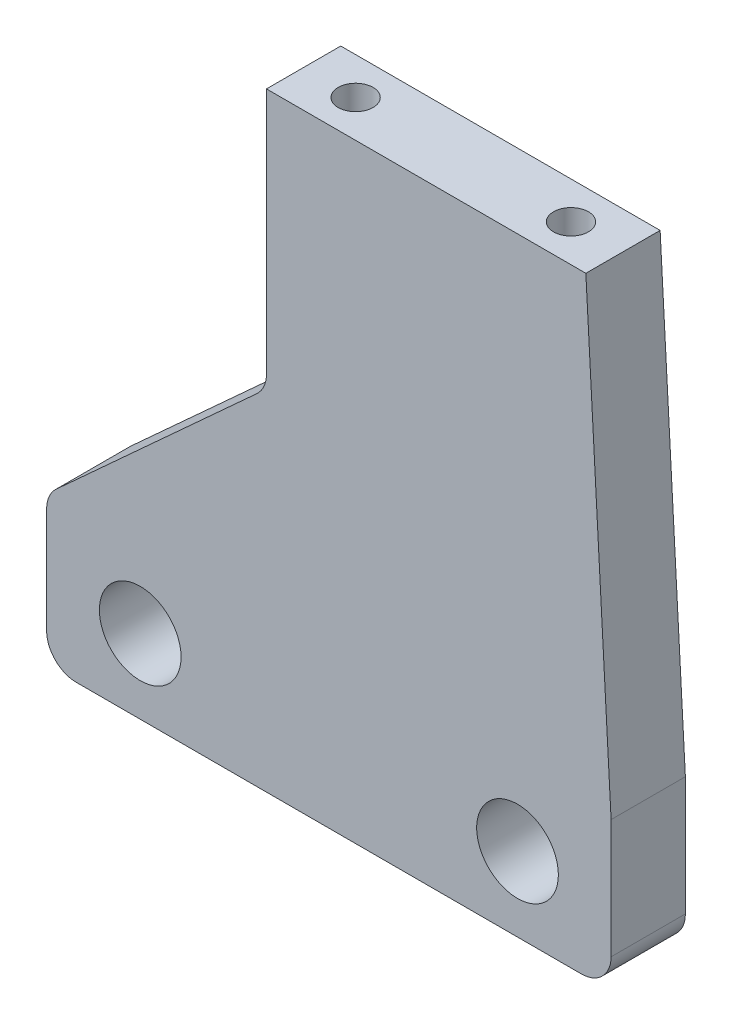
SolidWorks part; units mm, degrees
ref_plane "Front Plane" through (0, 0, 0) normal (0, 0, 1) x (1, 0, 0)
ref_plane "Top Plane" through (0, 0, 0) normal (0, 1, 0) x (1, 0, 0)
ref_plane "Right Plane" through (0, 0, 0) normal (1, 0, 0) x (0, 0, -1)
sketch "Sketch1" plane through (0, 0, 0) normal (0, 0, 1) x (1, 0, 0)
  line L1 (-19, 5) -> (19, 5)
  line L2 (-19, 5) -> (-19, -5)
  line L3 (-19, -5) -> (19, -5)
  line L4 (19, 5) -> (19, -5)
  line L5 (-19, 5) -> (19, -5) construction
  line L6 (-19, -5) -> (19, 5) construction
  point P0 (0, 0)
  dimension "D1" = 38
  dimension "D2" = 10
extrude "Boss-Extrude1" add sketch "Sketch1" along normal blind 5
sketch "Sketch2" plane through (0, 0, 5) normal (0, 0, 1) x (1, 0, 0)
  line L0 (-19, 0) -> (19, 0) construction
  line L1 (-19, 5) -> (-19, -5) construction
  line L2 (19, -5) -> (19, 5) construction
  line L3 (0, 5) -> (0, -5) construction
  line L4 (19, 5) -> (-19, 5) construction
  line L5 (-19, -5) -> (19, -5) construction
  circle A0 centre (-12.7, 0) radius 2.75
  circle A1 centre (12.7, 0) radius 2.75
  dimension "D3" = 5.5
  dimension "D4" = 5.5
  dimension "D1" = 12.7
  dimension "D2" = 12.7
extrude "Cut-Extrude1" cut sketch "Sketch2" against normal blind 5
sketch "Sketch3" plane through (0, 0, 5) normal (0, 0, 1) x (1, 0, 0)
  line L0 (-19, 0) -> (19, 0) construction
  line L1 (17.3, 5) -> (-4.2, 5)
  line L2 (17.3, 5) -> (17.3, 36)
  line L3 (17.3, 36) -> (-4.2, 36)
  line L4 (-4.2, 5) -> (-4.2, 36)
  line L5 (-19, 5) -> (-19, -5) construction
  line L6 (19, -5) -> (19, 5) construction
  line L7 (19, 5) -> (-19, 5) construction
  dimension "D1" = 21.5
  dimension "D2" = 36
  dimension "D3" = 1.7
extrude "Boss-Extrude2" add sketch "Sketch3" against normal blind 5
sketch "Sketch8" plane through (0, 0, 5) normal (0, 0, 1) x (1, 0, 0)
  line L0 (-4.2, 5) -> (-19, 5)
  line L1 (-19, 5) -> (-4.2, 18.5)
  line L2 (-4.2, 36) -> (-4.2, 5) construction
  line L3 (-4.2, 18.5) -> (-4.2, 5)
  dimension "D1" = 13.5
extrude "Boss-Extrude6" add sketch "Sketch8" against normal blind 5
sketch "Sketch10" plane through (0, 36, 0) normal (0, 1, 0) x (1, 0, 0)
  line L0 (-4.2, -2.5) -> (17.3, -2.5) construction
  line L1 (-4.2, 0) -> (-4.2, -5) construction
  line L2 (17.3, 0) -> (17.3, -5) construction
  circle A0 centre (-0.7, -2.5) radius 1.175
  circle A1 centre (13.8, -2.5) radius 1.175
  dimension "D1" = 2.35
  dimension "D2" = 2.35
  dimension "D3" = 3.5
  dimension "D4" = 3.5
extrude "Cut-Extrude4" cut sketch "Sketch10" against normal blind 8
fillet "Fillet2" radius 2 4 edges at (-19, -5, 2.5) (19, -5, 2.5) (-4.2, 18.5, 2.5) (-19, 5, 2.5)
sketch "Sketch11" plane through (0, 0, 5) normal (0, 0, 1) x (1, 0, 0)
  line L0 (19, 5) -> (17.3, 36)
  line L1 (17.3, 36) -> (17.3, 5)
  line L2 (17.3, 5) -> (17.3, 36) construction
  line L3 (19, 5) -> (17.3, 5) construction
  line L4 (17.3, 5) -> (19, 5)
extrude "Boss-Extrude7" add sketch "Sketch11" against normal blind 5
